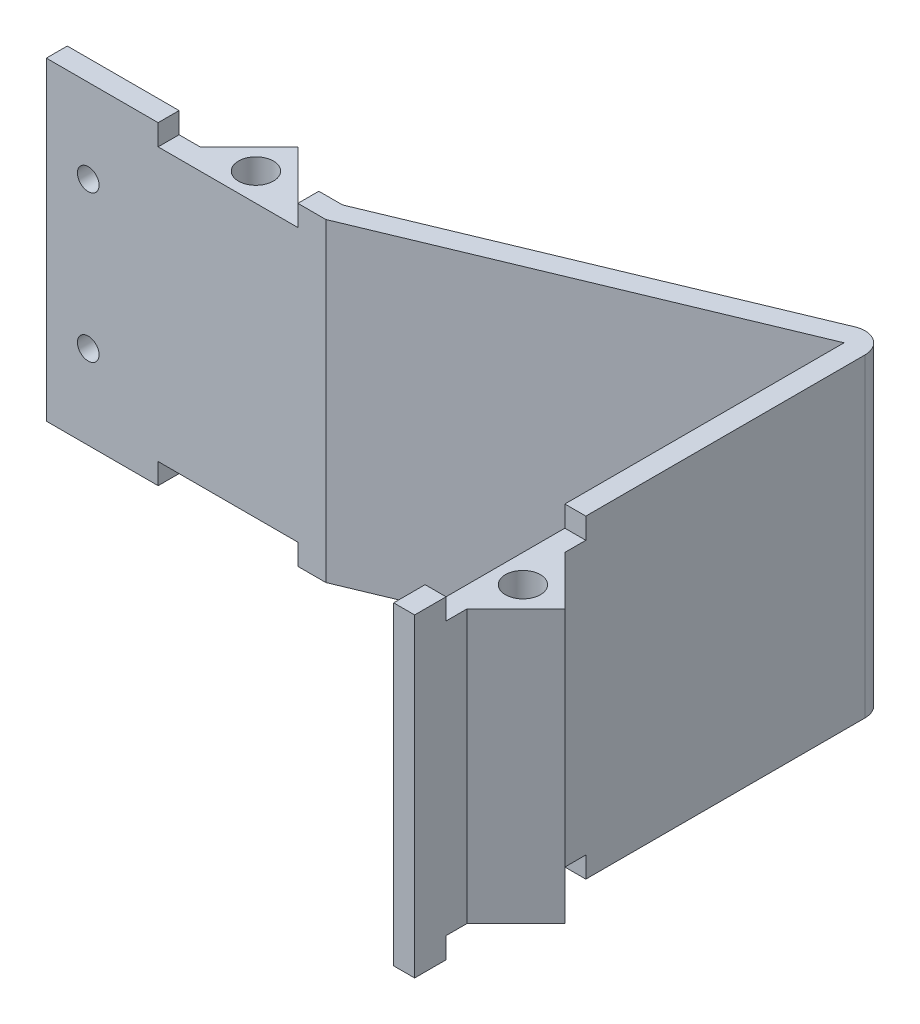
SolidWorks part; units mm, degrees
ref_plane "前视基准面" through (0, 0, 0) normal (0, 0, 1) x (1, 0, 0)
ref_plane "上视基准面" through (0, 0, 0) normal (0, 1, 0) x (1, 0, 0)
ref_plane "右视基准面" through (0, 0, 0) normal (1, 0, 0) x (0, 0, -1)
sketch "草图1" plane through (0, 0, 0) normal (0, 0, 1) x (1, 0, 0)
  line L1 (0, 0) -> (60, 0)
  line L2 (0, 0) -> (0, 45)
  line L3 (0, 45) -> (60, 45)
  line L4 (60, 0) -> (60, 45)
  dimension "D1" = 60
  dimension "D2" = 45
extrude "凸台-拉伸1" add sketch "草图1" along normal blind 3
sketch "草图2" plane through (0, 0, 3) normal (0, 0, 1) x (1, 0, 0)
  line L0 (0, 45) -> (0, 0) construction
  line L1 (0, 42) -> (60, 42)
  line L2 (0, 42) -> (0, 39)
  line L3 (0, 39) -> (60, 39)
  line L4 (60, 42) -> (60, 39)
  line L5 (60, 0) -> (60, 45) construction
  line L6 (60, 45) -> (0, 45) construction
  line L7 (0, 22.5) -> (60, 22.5) construction
  line L8 (0, 6) -> (60, 6)
  line L9 (60, 3) -> (60, 6)
  line L10 (0, 3) -> (60, 3)
  line L11 (0, 3) -> (0, 6)
  dimension "D1" = 3
  dimension "D2" = 3
extrude "凸台-拉伸2" add sketch "草图2" along normal blind 3
sketch "草图3" plane through (0, 0, 3) normal (0, 0, 1) x (1, 0, 0)
  line L0 (60, 45) -> (0, 45) construction
  line L1 (9.4025, 45) -> (19.0384, 45) construction
  line L2 (9.4025, 45) -> (9.4025, 42) construction
  line L3 (9.4025, 42) -> (19.0384, 42) construction
  line L4 (19.0384, 45) -> (19.0384, 42) construction
  line L5 (60, 42) -> (0, 42) construction
  line L6 (0, 3) -> (60, 3) construction
  line L7 (16, 3) -> (36, 3)
  line L8 (16, 3) -> (16, 0)
  line L9 (16, 0) -> (36, 0)
  line L10 (36, 3) -> (36, 0)
  line L11 (0, 0) -> (60, 0) construction
  line L13 (0, 3) -> (0, 0) construction
  line L14 (0, 22.5) -> (60, 22.5) construction
  line L15 (0, 39) -> (0, 6) construction
  line L16 (60, 6) -> (60, 39) construction
  line L17 (16, 45) -> (36, 45)
  line L18 (36, 42) -> (36, 45)
  line L19 (16, 42) -> (36, 42)
  line L20 (16, 42) -> (16, 45)
  dimension "D1" = 16
  dimension "D2" = 20
extrude "切除-拉伸1" cut sketch "草图3" against normal blind 3
sketch "草图4" plane through (0, 3, 0) normal (0, -1, 0) x (1, 0, 0)
  line L0 (19, 0) -> (26, -7)
  line L1 (26, -7) -> (26, 3) construction
  line L2 (36, 3) -> (26, 3) construction
  line L3 (26, 15.1904) -> (26, 3) construction
  line L4 (33, 0) -> (26, -7)
  line L5 (26, 3) -> (26, -7) construction
  line L6 (26, -7) -> (26, -12.6826) construction
  line L7 (33, 0) -> (19, 0)
  line L8 (36, 0) -> (16, 0) construction
  line L9 (26, 3) -> (16, 3) construction
  line L10 (16, 3) -> (19, 0) construction
  line L11 (36, 3) -> (33, 0) construction
  dimension "D1" = 10
  dimension "D2" = 10
extrude "凸台-拉伸3" add sketch "草图4" against normal up to vertex
sketch "草图5" plane through (0, 3, 0) normal (0, -1, 0) x (1, 0, 0)
  circle A0 centre (26, -1) radius 2.5
  dimension "D1" = 5
  dimension "D2" = 6
  dimension "D3" = 7
extrude "切除-拉伸2" cut sketch "草图5" against normal through all
sketch "草图6" plane through (0, 3, 0) normal (0, -1, 0) x (1, 0, 0)
  line L1 (0, 6) -> (60, 6)
  line L2 (0, 6) -> (0, 3)
  line L3 (0, 3) -> (60, 3)
  line L4 (60, 6) -> (60, 3)
extrude "切除-拉伸3" cut sketch "草图6" against normal through all
sketch "草图8" plane through (0, 0, 0) normal (0, -1, 0) x (1, 0, 0)
  line L0 (36, 0) -> (60, 0) construction
  line L1 (60, 3) -> (40, 3)
  line L2 (60, 3) -> (60, 0)
  line L3 (60, 0) -> (40, 0)
  line L4 (40, 3) -> (40, 0)
  line L5 (0, 3) -> (0, 0) construction
  dimension "D1" = 40
extrude "切除-拉伸4" cut sketch "草图8" against normal through all
sketch "草图9" plane through (0, 45, 0) normal (0, 1, 0) x (1, 0, 0)
  line L0 (40, -3) -> (92.37, 18.8)
  line L1 (38.8471, -0.2304) -> (91.2171, 21.5696)
  line L2 (38.8471, -0.2304) -> (40, -3)
  line L3 (91.2171, 21.5696) -> (92.37, 18.8)
  dimension "D1" = 21.8
  dimension "D2" = 52.37
  dimension "D3" = 3
extrude "凸台-拉伸4" add sketch "草图9" against normal through all
sketch "草图10" plane through (0, 45, 0) normal (0, 1, 0) x (1, 0, 0)
  line L0 (92.37, 18.8) -> (91.2171, 21.5696)
  line L1 (92.37, 18.8) -> (95.37, 18.8) construction
  line L2 (92.37, 18.8) -> (92.37, -45.66)
  line L3 (92.37, -45.66) -> (95.37, -45.66)
  line L4 (95.37, 18.8) -> (95.37, -45.66)
  arc A0 (95.37, 18.8) -> (91.2171, 21.5696) centre (92.37, 18.8) ccw
  arc A1 (91.2171, 21.5696) -> (92.37, 15.8) centre (92.37, 18.8) ccw construction
  arc A2 (92.37, 15.8) -> (95.37, 18.8) centre (92.37, 18.8) ccw construction
  dimension "D1" = 64.46
extrude "凸台-拉伸5" add sketch "草图10" against normal through all
sketch "草图11" plane through (95.37, 0, 0) normal (1, 0, 0) x (0, 0, -1)
  line L0 (-45.66, 0) -> (18.8, 0) construction
  line L1 (-41.16, 0) -> (-21.16, 0)
  line L2 (-41.16, 0) -> (-41.16, 3)
  line L3 (-41.16, 3) -> (-21.16, 3)
  line L4 (-21.16, 0) -> (-21.16, 3)
  line L5 (-45.66, 0) -> (-45.66, 45) construction
  line L6 (-45.66, 22.5) -> (18.8, 22.5) construction
  line L7 (18.8, 0) -> (18.8, 45) construction
  line L8 (-41.16, 42) -> (-21.16, 42)
  line L9 (-21.16, 45) -> (-21.16, 42)
  line L10 (-41.16, 45) -> (-21.16, 45)
  line L11 (-41.16, 45) -> (-41.16, 42)
  dimension "D1" = 3
  dimension "D2" = 20
  dimension "D3" = 4.5
extrude "切除-拉伸5" cut sketch "草图11" against normal blind 3
sketch "草图12" plane through (0, 42, 0) normal (0, 1, 0) x (1, 0, 0)
  line L4 (92.37, -21.16) -> (102.37, -31.16)
  line L8 (92.37, -41.16) -> (92.37, -21.16)
  line L9 (80.5429, -31.16) -> (92.37, -31.16) construction
  line L10 (92.37, -41.16) -> (102.37, -31.16)
  line L11 (102.37, -31.16) -> (131.6755, -31.16) construction
extrude "凸台-拉伸6" add sketch "草图12" against normal up to vertex
sketch "草图14" plane through (0, 42, 0) normal (0, 1, 0) x (1, 0, 0)
  line L0 (92.37, -41.16) -> (92.37, -21.16) construction
  line L1 (84.783, -31.16) -> (114.5744, -31.16) construction
  line L2 (92.37, -21.16) -> (95.37, -21.16) construction
  circle A0 centre (96.37, -31.16) radius 2.5
  dimension "D1" = 5
  dimension "D2" = 4
  dimension "D3" = 10
extrude "切除-拉伸7" cut sketch "草图14" against normal through all
sketch "草图16" plane through (0, 0, 0) normal (0, 0, -1) x (-1, 0, 0)
  line L0 (0, 22.5) -> (-19, 22.5) construction
  line L1 (0, 45) -> (0, 0) construction
  line L2 (-19, 42) -> (-19, 3) construction
  line L3 (-16, 45) -> (0, 45) construction
  circle A0 centre (-6, 33) radius 1.55
  circle A1 centre (-6, 12) radius 1.55
  dimension "D1" = 3.1
  dimension "D2" = 12
  dimension "D3" = 6
extrude "切除-拉伸8" cut sketch "草图16" against normal up to next
